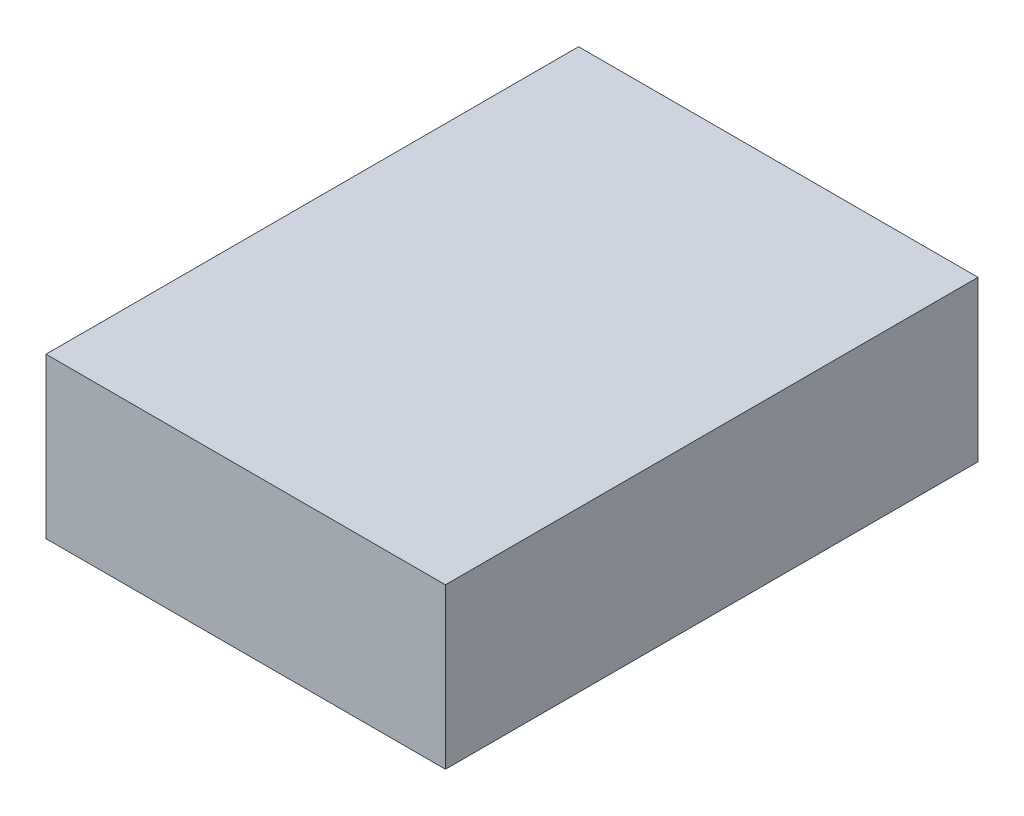
SolidWorks part; units mm, degrees
material "Acrilico TEC"
ref_plane "Front Plane" through (0, 0, 0) normal (0, 0, 1) x (1, 0, 0)
ref_plane "Top Plane" through (0, 0, 0) normal (0, 1, 0) x (1, 0, 0)
ref_plane "Right Plane" through (0, 0, 0) normal (1, 0, 0) x (0, 0, -1)
sketch "Sketch5" plane through (0, 0, 0) normal (0, 1, 0) x (1, 0, 0)
  line L1 (0, 0) -> (15, 0)
  line L2 (0, 0) -> (0, 20)
  line L3 (0, 20) -> (15, 20)
  line L4 (15, 0) -> (15, 20)
  dimension "D1" = 15
  dimension "D2" = 20
extrude "Boss-Extrude2" add sketch "Sketch5" along normal blind 6
